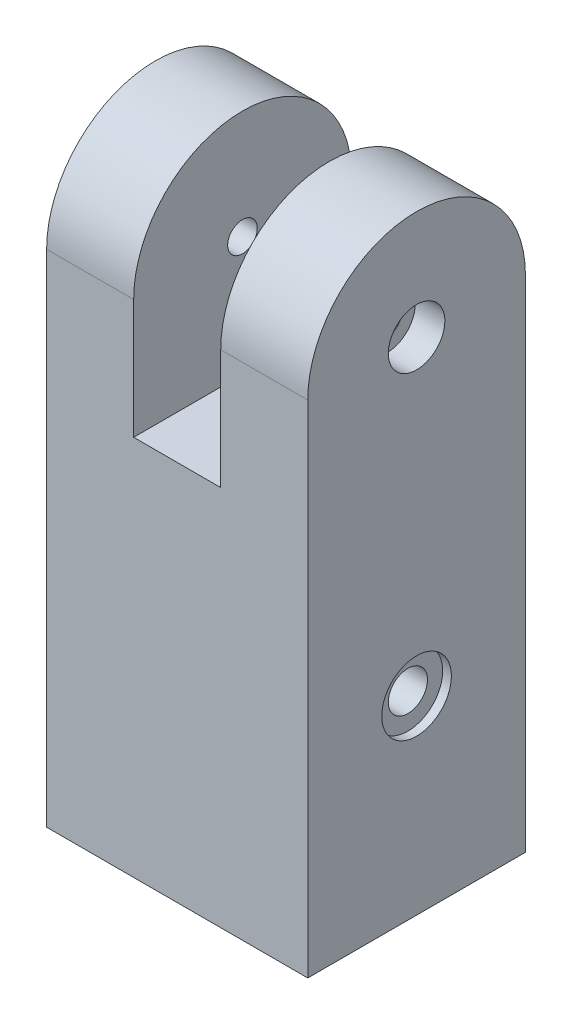
SolidWorks part; units mm, degrees
ref_plane "Plan de face" through (0, 0, 0) normal (0, 0, 1) x (1, 0, 0)
ref_plane "Plan de dessus" through (0, 0, 0) normal (0, 1, 0) x (1, 0, 0)
ref_plane "Plan de droite" through (0, 0, 0) normal (1, 0, 0) x (0, 0, -1)
sketch "Esquisse1" plane through (0, 0, 0) normal (1, 0, 0) x (0, 0, -1)
  line L0 (-12.5, -40.2999) -> (-12.5, 17.2001)
  line L1 (12.5, 17.2001) -> (12.5, -40.2999)
  line L2 (12.5, -40.2999) -> (-12.5, -40.2999)
  arc A0 (-12.5, 17.2001) -> (12.5, 17.2001) centre (0, 17.2001) cw
  dimension "D2" = 25
extrude "Boss.-Extru.1" add sketch "Esquisse1" along normal mid plane 30
hole_wizard "Chambrage pour vis à tête hexagonale M31" positions "Esquisse4" profile "Esquisse5" counterbore size "M3" standard "ISO"
sketch "Esquisse4" plane through (15, 0, 0) normal (1, 0, 0) x (0, 0, -1)
  point P0 (0, 17.2001)
sketch "Esquisse5" plane through (15, 17.2001, 0) normal (0, 1, 0) x (0, 0, -1)
  line L0 (0, 0) -> (0, 31.0205)
  line L1 (0, 31.0205) -> (1.7, 29.999)
  line L2 (1.7, 29.999) -> (1.7, 3.4)
  line L3 (1.7, 3.4) -> (3.25, 3.4)
  line L4 (3.25, 3.4) -> (3.25, 0)
  line L5 (3.25, 0) -> (0, 0)
  line L10 (0, 31.0205) -> (-1.7, 29.999) construction
  line L11 (0, -6.35) -> (0, 107.95) construction
  dimension "Diamètre du perçage" = 3.4
  dimension "Profondeur du perçage" = 29.999
  dimension "Diamètre du chambrage" = 6.5
  dimension "Profondeur du chambrage" = 3.4
  dimension "Angle de pointe" = 118
sketch "Esquisse7" plane through (15, 0, 0) normal (1, 0, 0) x (0, 0, -1)
  circle A0 centre (0, 17.2001) radius 12.5 construction
sketch "Esquisse3" plane through (0, 0, -12.5) normal (0, 0, -1) x (-1, 0, 0)
  line L0 (15, 29.7001) -> (-15, 29.7001) construction
  line L1 (-5, 29.7001) -> (5, 29.7001)
  line L2 (-5, 29.7001) -> (-5, 3.4921)
  line L3 (-5, 3.4921) -> (5, 3.4921)
  line L4 (5, 29.7001) -> (5, 3.4921)
  point P6 (0, 3.4921)
  dimension "D2" = 10
extrude "Enlèv. mat.-Extru.2" cut sketch "Esquisse3" against normal up to next
sketch "Esquisse2" plane through (0, -40.2999, 0) normal (0, -1, 0) x (1, 0, 0)
  line L1 (-10.2, 10.2) -> (10.2, 10.2)
  line L2 (-10.2, 10.2) -> (-10.2, -10.2)
  line L3 (-10.2, -10.2) -> (10.2, -10.2)
  line L4 (10.2, 10.2) -> (10.2, -10.2)
  line L5 (-10.2, 10.2) -> (10.2, -10.2) construction
  line L6 (-10.2, -10.2) -> (10.2, 10.2) construction
  point P0 (0, 0)
  dimension "D1" = 20.4
  dimension "D2" = 20.4
extrude "Enlèv. mat.-Extru.1" cut sketch "Esquisse2" against normal offset from surface (38.7919 mm away) 5 up to face at (0, 3.4921, 0)
hole_wizard "Chambrage pour vis à tête hexagonale M42" positions "Esquisse9" profile "Esquisse10" counterbore size "M4" standard "ISO"
sketch "Esquisse9" plane through (-15, 0, 0) normal (-1, 0, 0) x (0, 0, 1)
  point P0 (0, -18.495)
sketch "Esquisse10" plane through (-15, -18.495, 0) normal (0, 1, 0) x (0, 0, 1)
  line L0 (0, 0) -> (0, 4.8)
  line L1 (0, 4.8) -> (2.25, 4.8)
  line L3 (2.25, 4.8) -> (2.25, 1)
  line L4 (2.25, 1) -> (4, 1)
  line L5 (4, 1) -> (4, 0)
  line L7 (4, 0) -> (0, 0)
  line L11 (0, -6.35) -> (0, 107.95) construction
  dimension "Diamètre du perçage jusqu'au prochain" = 4.5
  dimension "Profondeur du perçage jusqu'au prochain" = 4.8
  dimension "Diamètre du chambrage" = 8
  dimension "Profondeur du chambrage" = 1
hole_wizard "Chambrage pour vis à tête hexagonale M43" positions "Esquisse11" profile "Esquisse12" counterbore size "M4" standard "ISO" end condition up to next
sketch "Esquisse11" plane through (0, 3.4921, 0) normal (0, 1, 0) x (1, 0, 0)
  point P0 (0, 0)
sketch "Esquisse12" plane through (0, 3.4921, 0) normal (1, 0, 0) x (0, 0, 1)
  line L0 (0, 0) -> (0, 5)
  line L1 (0, 5) -> (2.25, 5)
  line L3 (2.25, 5) -> (2.25, 4.4)
  line L4 (2.25, 4.4) -> (4, 4.4)
  line L5 (4, 4.4) -> (4, 0)
  line L7 (4, 0) -> (0, 0)
  line L11 (0, -6.35) -> (0, 107.95) construction
  dimension "Diamètre du perçage jusqu'au prochain" = 4.5
  dimension "Profondeur du perçage jusqu'au prochain" = 5
  dimension "Diamètre du chambrage" = 8
  dimension "Profondeur du chambrage" = 4.4
mirror "Symétrie1" about plane through (0, 0, 0) normal (1, 0, 0) of "Chambrage pour vis à tête hexagonale M42"
